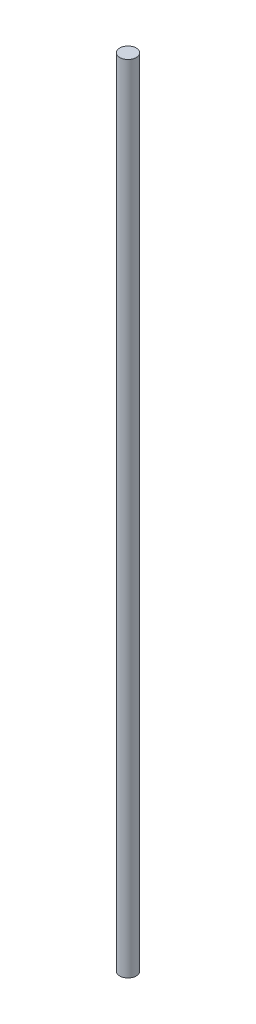
SolidWorks part; units mm, degrees
ref_plane "Front Plane" through (0, 0, 0) normal (0, 0, 1) x (1, 0, 0)
ref_plane "Top Plane" through (0, 0, 0) normal (0, 1, 0) x (1, 0, 0)
ref_plane "Right Plane" through (0, 0, 0) normal (1, 0, 0) x (0, 0, -1)
sketch "Sketch1" plane through (0, 0, 0) normal (0, 1, 0) x (1, 0, 0)
  circle A0 centre (0, 0) radius 4
  dimension "D1" = 8
extrude "Boss-Extrude1" add sketch "Sketch1" along normal blind 385 contours A0
